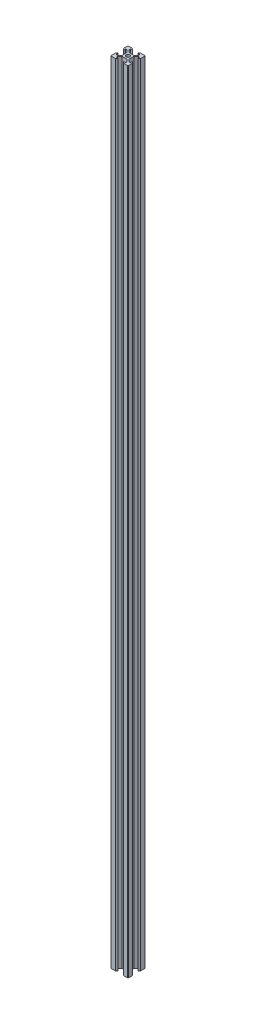
SolidWorks part; units mm, degrees
ref_plane "Front Plane" through (0, 0, 0) normal (0, 0, 1) x (1, 0, 0)
ref_plane "Top Plane" through (0, 0, 0) normal (0, 1, 0) x (1, 0, 0)
ref_plane "Right Plane" through (0, 0, 0) normal (1, 0, 0) x (0, 0, -1)
sketch "Sketch1" plane through (0, 0, 0) normal (1, 0, 0) x (0, 0, -1)
  line L0 (0, 0) -> (0, 914.4)
  dimension "D1" = 914.4
other "Vslot2020 2020(5)"
ref_plane "Plane5" through (0, 0, 0) normal (0, 1, 0) x (0, 0, 1)
sketch "Sketch2" plane through (0, 0, 0) normal (0, 1, 0) x (0, 0, 1)
  line L58 (13.9, 7.1491) -> (13.9, 12.8445)
  line L59 (13.9, 12.8445) -> (16.5585, 15.4922)
  line L60 (16.5585, 15.4922) -> (16.5507, 15.5)
  line L61 (16.5507, 15.5) -> (18.2, 15.5)
  line L62 (18.2, 15.5) -> (18.2, 13.12)
  line L63 (18.2, 13.12) -> (18.5344, 13.12)
  line L64 (18.5344, 13.12) -> (20, 14.58)
  line L65 (20, 14.58) -> (20, 19.5)
  line L66 (19.5, 20) -> (14.575, 20)
  line L67 (14.575, 20) -> (13.12, 18.545)
  line L68 (13.12, 18.545) -> (13.12, 18.2)
  line L69 (13.12, 18.2) -> (15.5, 18.2)
  line L70 (15.5, 18.2) -> (15.5, 16.555)
  line L71 (15.5, 16.555) -> (12.8341, 13.9)
  line L72 (12.8341, 13.9) -> (7.155, 13.9)
  line L73 (7.155, 13.9) -> (4.5, 16.555)
  line L74 (4.5, 16.555) -> (4.5, 18.2)
  line L75 (4.5, 18.2) -> (6.875, 18.2)
  line L76 (6.875, 18.2) -> (6.875, 18.545)
  line L77 (6.875, 18.545) -> (5.42, 20)
  line L78 (5.42, 20) -> (0.5, 20)
  line L79 (0, 19.5) -> (0, 14.58)
  line L80 (0, 14.58) -> (1.46, 13.12)
  line L81 (1.46, 13.12) -> (1.8, 13.12)
  line L82 (1.8, 13.12) -> (1.8, 15.5)
  line L83 (1.8, 15.5) -> (3.445, 15.5)
  line L84 (3.445, 15.5) -> (3.4393, 15.4943)
  line L85 (3.4393, 15.4943) -> (6.0943, 12.8393)
  line L86 (6.0943, 12.8393) -> (6.1, 12.845)
  line L87 (6.1, 12.845) -> (6.1, 7.1491)
  line L88 (6.1, 7.1491) -> (3.4393, 4.5)
  line L89 (3.4393, 4.5) -> (1.8, 4.5)
  line L90 (1.8, 4.5) -> (1.8, 6.88)
  line L91 (1.8, 6.88) -> (1.46, 6.88)
  line L92 (1.46, 6.88) -> (0, 5.42)
  line L93 (0, 5.42) -> (0, 0.5)
  line L94 (0.5, 0) -> (5.42, 0)
  line L95 (5.42, 0) -> (6.875, 1.455)
  line L96 (6.875, 1.455) -> (6.875, 1.8)
  line L97 (6.875, 1.8) -> (4.5, 1.8)
  line L98 (4.5, 1.8) -> (4.5, 3.4393)
  line L99 (4.5, 3.4393) -> (7.1583, 6.0861)
  line L100 (7.1583, 6.0861) -> (7.1445, 6.1)
  line L101 (7.1445, 6.1) -> (12.8546, 6.1)
  line L102 (12.8546, 6.1) -> (12.8412, 6.0865)
  line L103 (12.8412, 6.0865) -> (15.4997, 3.4375)
  line L104 (15.4997, 3.4375) -> (15.5, 3.4377)
  line L105 (15.5, 3.4377) -> (15.5, 1.8)
  line L106 (15.5, 1.8) -> (13.12, 1.8)
  line L107 (13.12, 1.8) -> (13.12, 1.455)
  line L108 (13.12, 1.455) -> (14.575, 0)
  line L109 (14.575, 0) -> (19.5, 0)
  line L110 (20, 0.5) -> (20, 5.42)
  line L111 (20, 5.42) -> (18.6069, 6.88)
  line L112 (18.6069, 6.88) -> (18.2, 6.88)
  line L113 (18.2, 6.88) -> (18.2, 4.5)
  line L114 (18.2, 4.5) -> (16.5585, 4.5)
  line L115 (16.5585, 4.5) -> (13.9, 7.1491)
  line L116 (13.9, 7.1491) -> (13.9, 12.8445)
  line L117 (13.9, 12.8445) -> (16.5585, 15.4922)
  line L118 (16.5585, 15.4922) -> (16.5507, 15.5)
  line L119 (16.5507, 15.5) -> (18.2, 15.5)
  line L120 (18.2, 15.5) -> (18.2, 13.12)
  line L121 (18.2, 13.12) -> (18.5344, 13.12)
  line L122 (18.5344, 13.12) -> (20, 14.58)
  line L123 (20, 14.58) -> (20, 19.5)
  line L124 (19.5, 20) -> (14.575, 20)
  line L125 (14.575, 20) -> (13.12, 18.545)
  line L126 (13.12, 18.545) -> (13.12, 18.2)
  line L127 (13.12, 18.2) -> (15.5, 18.2)
  line L128 (15.5, 18.2) -> (15.5, 16.555)
  line L129 (15.5, 16.555) -> (12.8341, 13.9)
  line L130 (12.8341, 13.9) -> (7.155, 13.9)
  line L131 (7.155, 13.9) -> (4.5, 16.555)
  line L132 (4.5, 16.555) -> (4.5, 18.2)
  line L133 (4.5, 18.2) -> (6.875, 18.2)
  line L134 (6.875, 18.2) -> (6.875, 18.545)
  line L135 (6.875, 18.545) -> (5.42, 20)
  line L136 (5.42, 20) -> (0.5, 20)
  line L137 (0, 19.5) -> (0, 14.58)
  line L138 (0, 14.58) -> (1.46, 13.12)
  line L139 (1.46, 13.12) -> (1.8, 13.12)
  line L140 (1.8, 13.12) -> (1.8, 15.5)
  line L141 (1.8, 15.5) -> (3.445, 15.5)
  line L142 (3.445, 15.5) -> (3.4393, 15.4943)
  line L143 (3.4393, 15.4943) -> (6.0943, 12.8393)
  line L144 (6.0943, 12.8393) -> (6.1, 12.845)
  line L145 (6.1, 12.845) -> (6.1, 7.1491)
  line L146 (6.1, 7.1491) -> (3.4393, 4.5)
  line L147 (3.4393, 4.5) -> (1.8, 4.5)
  line L148 (1.8, 4.5) -> (1.8, 6.88)
  line L149 (1.8, 6.88) -> (1.46, 6.88)
  line L150 (1.46, 6.88) -> (0, 5.42)
  line L151 (0, 5.42) -> (0, 0.5)
  line L152 (0.5, 0) -> (5.42, 0)
  line L153 (5.42, 0) -> (6.875, 1.455)
  line L154 (6.875, 1.455) -> (6.875, 1.8)
  line L155 (6.875, 1.8) -> (4.5, 1.8)
  line L156 (4.5, 1.8) -> (4.5, 3.4393)
  line L157 (4.5, 3.4393) -> (7.1583, 6.0861)
  line L158 (7.1583, 6.0861) -> (7.1445, 6.1)
  line L159 (7.1445, 6.1) -> (12.8546, 6.1)
  line L160 (12.8546, 6.1) -> (12.8412, 6.0865)
  line L161 (12.8412, 6.0865) -> (15.4997, 3.4375)
  line L162 (15.4997, 3.4375) -> (15.5, 3.4377)
  line L163 (15.5, 3.4377) -> (15.5, 1.8)
  line L164 (15.5, 1.8) -> (13.12, 1.8)
  line L165 (13.12, 1.8) -> (13.12, 1.455)
  line L166 (13.12, 1.455) -> (14.575, 0)
  line L167 (14.575, 0) -> (19.5, 0)
  line L168 (20, 0.5) -> (20, 5.42)
  line L169 (20, 5.42) -> (18.6069, 6.88)
  line L170 (18.6069, 6.88) -> (18.2, 6.88)
  line L171 (18.2, 6.88) -> (18.2, 4.5)
  line L172 (18.2, 4.5) -> (16.5585, 4.5)
  line L173 (16.5585, 4.5) -> (13.9, 7.1491)
  circle A0 centre (10, 10) radius 2.0746 construction
  circle A1 centre (10, 10) radius 2.0746
  arc A4 (20, 19.5) -> (19.5, 20) centre (19.5, 19.5) ccw
  arc A5 (0.5, 20) -> (0, 19.5) centre (0.5, 19.5) ccw
  arc A6 (0, 0.5) -> (0.5, 0) centre (0.5, 0.5) ccw
  arc A7 (19.5, 0) -> (20, 0.5) centre (19.5, 0.5) ccw
  arc A8 (20, 19.5) -> (19.5, 20) centre (19.5, 19.5) ccw
  arc A9 (0.5, 20) -> (0, 19.5) centre (0.5, 19.5) ccw
  arc A10 (0, 0.5) -> (0.5, 0) centre (0.5, 0.5) ccw
  arc A11 (19.5, 0) -> (20, 0.5) centre (19.5, 0.5) ccw
  point P16 (0, 0)
  dimension "D1" = 0
ref_plane "Plane6" through (9.997, 0, 0) normal (1, 0, 0) x (0, 0, -1)
ref_plane "Plane7" through (0, 0, 9.9946) normal (0, 0, 1) x (1, 0, 0)
